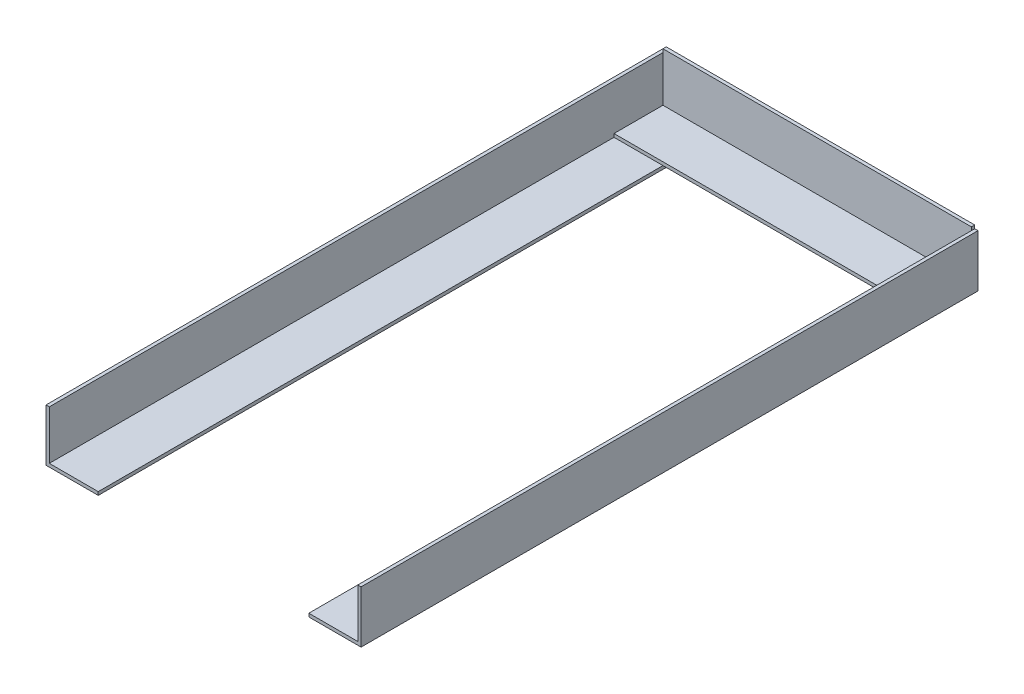
SolidWorks part; units mm, degrees
ref_plane "Front Plane" through (0, 0, 0) normal (0, 0, 1) x (1, 0, 0)
ref_plane "Top Plane" through (0, 0, 0) normal (0, 1, 0) x (1, 0, 0)
ref_plane "Right Plane" through (0, 0, 0) normal (1, 0, 0) x (0, 0, -1)
sketch "Sketch1" plane through (0, 0, 0) normal (0, 0, 1) x (1, 0, 0)
  line L0 (25.4, 0) -> (0, 0)
  line L1 (0, 0) -> (0, 25.4)
  line L2 (25.4, 1.6002) -> (1.6002, 1.6002)
  line L3 (1.6002, 1.6002) -> (1.6002, 25.4)
  line L4 (25.4, 0) -> (25.4, 1.6002)
  line L5 (0, 25.4) -> (1.6002, 25.4)
  line L6 (76.6002, 0) -> (76.6002, 25.4) construction
  line L7 (153.2004, 25.4) -> (151.6002, 25.4)
  line L8 (127.8004, 0) -> (127.8004, 1.6002)
  line L9 (151.6002, 1.6002) -> (151.6002, 25.4)
  line L10 (127.8004, 1.6002) -> (151.6002, 1.6002)
  line L11 (153.2004, 0) -> (153.2004, 25.4)
  line L12 (127.8004, 0) -> (153.2004, 0)
  dimension "D1" = 25.4
  dimension "D3" = 150
  dimension "D2" = 1.6002
extrude "Boss-Extrude1" add sketch "Sketch1" against normal blind 300
sketch "Sketch2" plane through (1.6002, 0, 0) normal (1, 0, 0) x (0, 0, -1)
  line L0 (274.6, 1.6002) -> (300, 1.6002)
  line L1 (300, 1.6002) -> (0, 1.6002) construction
  line L2 (300, 1.6002) -> (300, 27.0002)
  line L3 (274.6, 3.2004) -> (298.3998, 3.2004)
  line L4 (298.3998, 3.2004) -> (298.3998, 27.0002)
  line L5 (274.6, 1.6002) -> (274.6, 3.2004)
  line L6 (298.3998, 27.0002) -> (300, 27.0002)
  dimension "D2" = 25.4
  dimension "D1" = 1.6002
extrude "Boss-Extrude2" add sketch "Sketch2" along normal blind 150
